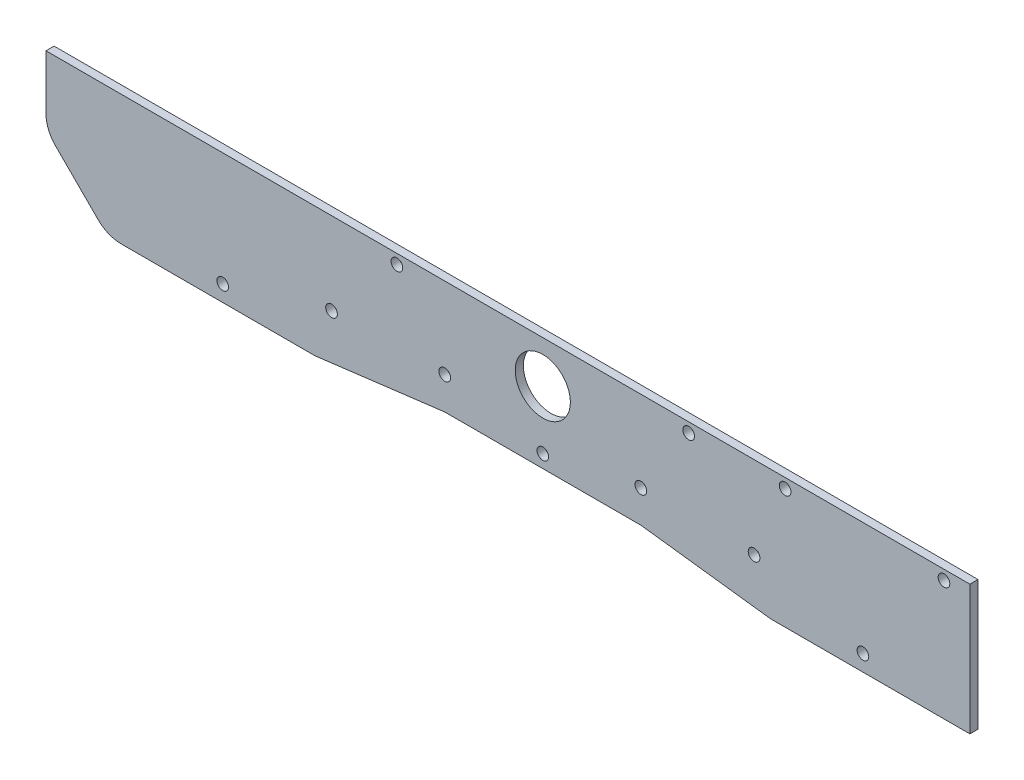
SolidWorks part; units mm, degrees
ref_plane "Front Plane" through (0, 0, 0) normal (0, 0, 1) x (1, 0, 0)
ref_plane "Top Plane" through (0, 0, 0) normal (0, 1, 0) x (1, 0, 0)
ref_plane "Right Plane" through (0, 0, 0) normal (1, 0, 0) x (0, 0, -1)
sketch "Sketch1" plane through (0, 0, 0) normal (0, 0, 1) x (1, 0, 0)
  line L0 (-205.74, 19.05) -> (-128.905, 19.05) construction
  line L1 (0, 0) -> (-361.95, 0)
  line L2 (0, 0) -> (0, 50.8)
  line L3 (0, 50.8) -> (-361.95, 50.8)
  line L4 (-361.95, 0) -> (-361.95, 50.8)
  line L5 (-167.3225, 6.35) -> (-167.3225, 34.29) construction
  line L6 (-292.735, 6.35) -> (-41.91, 6.35) construction
  line L7 (-292.735, 6.35) -> (-250.0852, 18.5066) construction
  line L8 (-250.0852, 18.5066) -> (-205.74, 19.05) construction
  circle A0 centre (-41.91, 6.35) radius 2.286
  circle A2 centre (-292.735, 6.35) radius 2.286
  circle A4 centre (-128.905, 19.05) radius 2.286
  circle A5 centre (-205.74, 19.05) radius 2.286
  circle A6 centre (-167.3225, 34.29) radius 10.795
  circle A7 centre (-250.0852, 18.5066) radius 2.286
  circle A8 centre (-84.5598, 18.5066) radius 2.286
  point P17 (-167.3225, 19.05)
  dimension "D3" = 6.35
  dimension "D5" = 4.572
  dimension "D6" = 76.835
  dimension "D9" = 12.7
  dimension "D10" = 21.59
  dimension "D11" = 4.572
  dimension "D1" = 50.8
  dimension "D2" = 361.95
  dimension "D4" = 41.91
  dimension "D7" = 250.825
  dimension "D8" = 27.94
  dimension "D13" = 44.3485
  dimension "D16" = 86.995
extrude "Boss-Extrude1" add sketch "Sketch1" along normal blind 3.175
sketch "Sketch2" plane through (0, 0, 3.175) normal (0, 0, 1) x (1, 0, 0)
  line L0 (-388.62, 50.8) -> (-337.82, 0)
  line L2 (-361.95, 0) -> (0, 0) construction
  line L3 (-388.62, 50.8) -> (-388.62, 0)
  line L4 (-388.62, 0) -> (-337.82, 0)
  line L5 (0, 0) -> (0, 50.8) construction
  line L6 (0, 50.8) -> (-361.95, 50.8) construction
  dimension "D1" = 50.8
  dimension "D2" = 337.82
extrude "Cut-Extrude1" cut sketch "Sketch2" against normal through all
fillet "Fillet1" radius 12.7 2 edges at (-337.82, 0, 1.5875) (-361.95, 24.13, 1.5875)
sketch "Sketch3" plane through (0, 0, 3.175) normal (0, 0, 1) x (1, 0, 0)
  line L0 (-256.54, 0) -> (-205.74, 6.35)
  line L1 (-332.5595, 0) -> (0, 0) construction
  line L2 (-205.74, 6.35) -> (-128.905, 6.35)
  line L3 (-128.905, 6.35) -> (-78.105, 0)
  line L4 (-78.105, 0) -> (-256.54, 0)
  point P4 (-128.905, 19.05)
  point P7 (-205.74, 19.05)
  dimension "D1" = 50.8
  dimension "D2" = 50.8
  dimension "D3" = 12.7
extrude "Cut-Extrude2" cut sketch "Sketch3" against normal through all
sketch "Sketch4" plane through (0, 0, 0) normal (0, 0, -1) x (-1, 0, 0)
  circle A0 centre (110.1725, 46.99) radius 2.286
  circle A1 centre (167.3225, 11.43) radius 2.286
  circle A2 centre (224.4725, 46.99) radius 2.286
  dimension "D1" = 4.572
extrude "Cut-Extrude3" cut sketch "Sketch4" against normal through all
sketch "Sketch6" plane through (0, 0, 3.175) normal (0, 0, 1) x (1, 0, 0)
  line L0 (0, 0) -> (0, 50.8) construction
  line L1 (0, 50.8) -> (-361.95, 50.8) construction
  circle A0 centre (-72.39, 46.99) radius 2.286
  circle A1 centre (-10.16, 46.99) radius 2.286
  dimension "D2" = 4.572
  dimension "D1" = 10.16
  dimension "D3" = 3.81
  dimension "D4" = 62.23
extrude "Cut-Extrude4" cut sketch "Sketch6" against normal through all
sketch "Sketch7" plane through (0, 0, 0) normal (0, 0, -1) x (-1, 0, 0)
  line L0 (17.78, 50.8) -> (17.78, 101.6)
  line L1 (0, 50.8) -> (361.95, 50.8) construction
  line L2 (0, 0) -> (0, 50.8) construction
  line L4 (43.18, 151.8586) -> (43.18, 50.8)
  line L5 (17.78, 50.8) -> (43.18, 50.8)
  line L6 (17.78, 101.6) -> (-14.3904, 117.3146)
  line L7 (17.78, 101.6) -> (16.972, 158.1575)
  line L8 (-14.3904, 117.3146) -> (-15.1983, 173.8721)
  line L9 (16.972, 158.1575) -> (-15.1983, 173.8721)
  circle A0 centre (25.4, 58.42) radius 2.286
  dimension "D5" = 4.572
  dimension "D1" = 17.78
  dimension "D2" = 25.4
  dimension "D3" = 50.8
  dimension "D4" = 7.62
  dimension "D6" = 25.4
